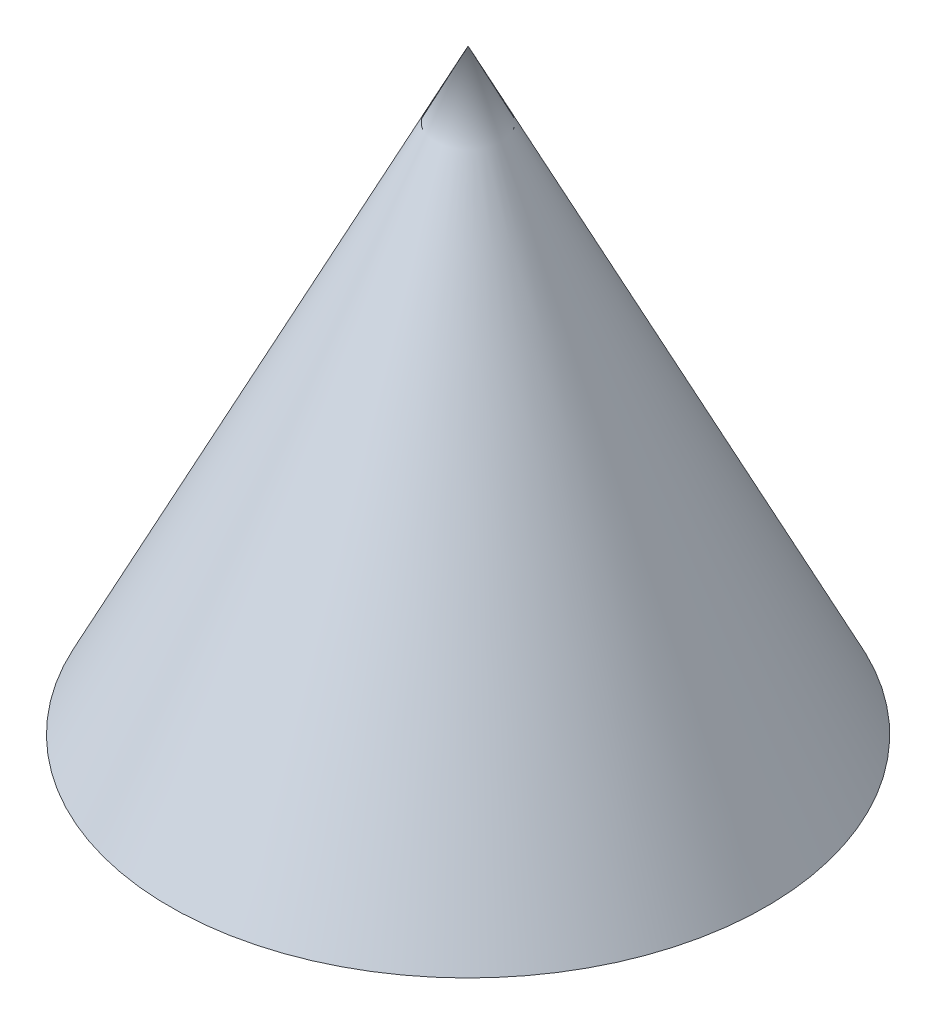
SolidWorks part; units mm, degrees
ref_plane "前视基准面" through (0, 0, 0) normal (0, 0, 1) x (1, 0, 0)
ref_plane "上视基准面" through (0, 0, 0) normal (0, 1, 0) x (1, 0, 0)
ref_plane "右视基准面" through (0, 0, 0) normal (1, 0, 0) x (0, 0, -1)
other "Configuration Table"
sketch "草图1" plane through (0, 0, 0) normal (0, 0, 1) x (1, 0, 0)
  line L0 (0, 0) -> (0, 100) construction
  line L1 (0, 0) -> (50, 0)
  line L2 (50, 0) -> (0, 100)
  line L3 (0, 100) -> (0, 0)
revolve "旋转1" add sketch "草图1" angle 360 about L0
